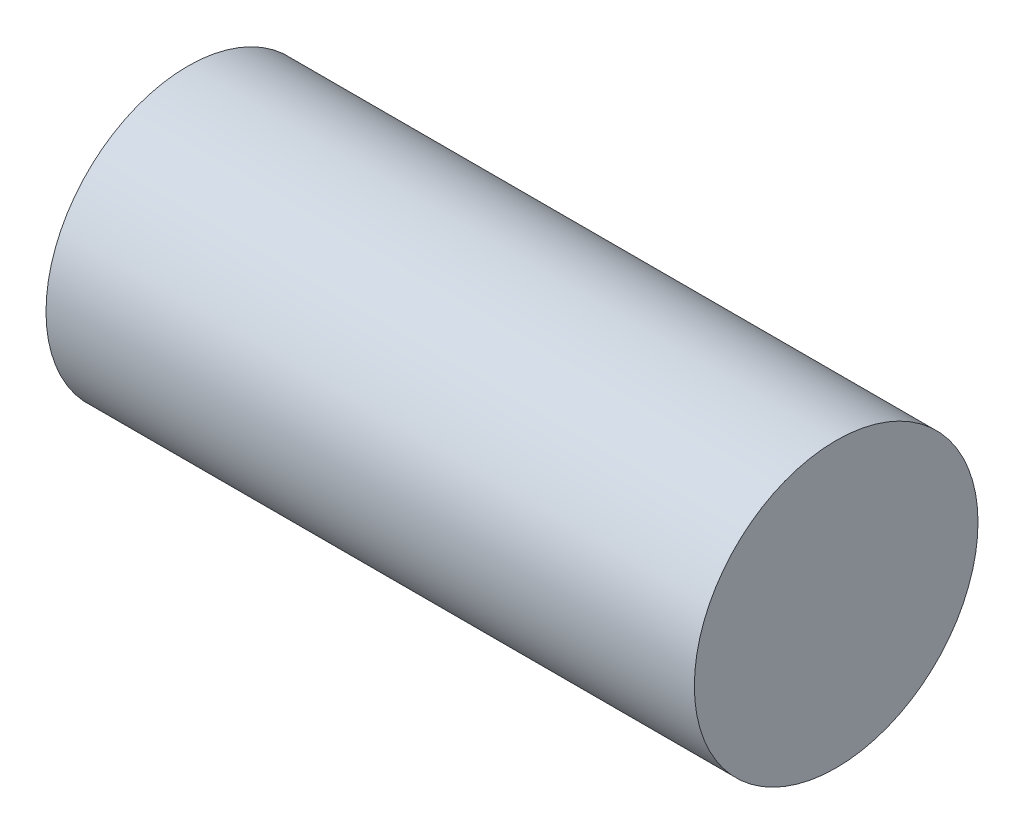
SolidWorks part; units mm, degrees
ref_plane "Front Plane" through (0, 0, 0) normal (0, 0, 1) x (1, 0, 0)
ref_plane "Top Plane" through (0, 0, 0) normal (0, 1, 0) x (1, 0, 0)
ref_plane "Right Plane" through (0, 0, 0) normal (1, 0, 0) x (0, 0, -1)
sketch "Sketch1" plane through (-60.382, 0, 0) normal (-1, 0, 0) x (0, 0, 1)
  circle A0 centre (-48.4768, 27.6717) radius 1.75
  dimension "D1" = 3.5
extrude "Boss-Extrude1" add sketch "Sketch1" along normal blind 8
